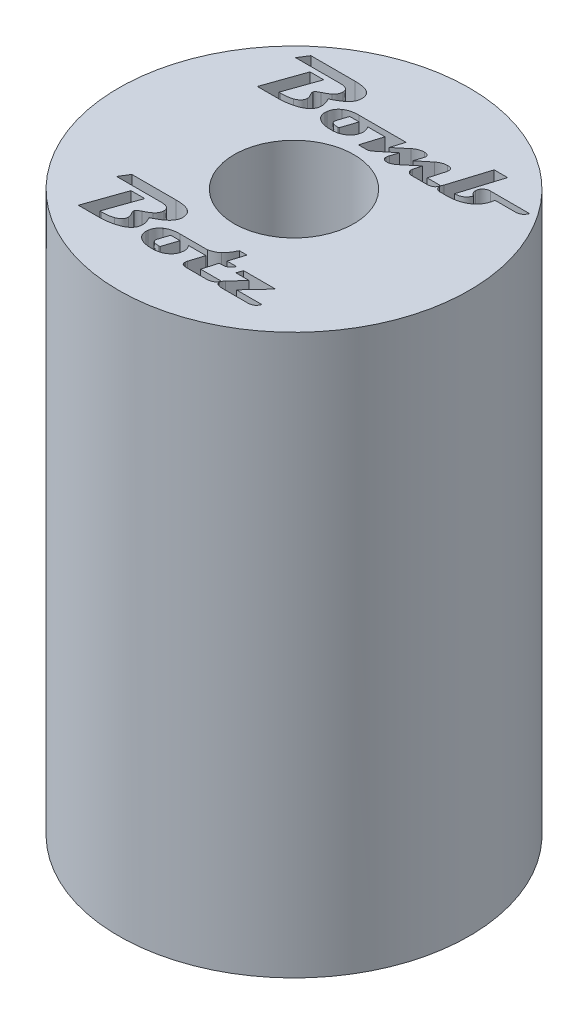
SolidWorks part; units mm, degrees
ref_plane "Front Plane" through (0, 0, 0) normal (0, 0, 1) x (1, 0, 0)
ref_plane "Top Plane" through (0, 0, 0) normal (0, 1, 0) x (1, 0, 0)
ref_plane "Right Plane" through (0, 0, 0) normal (1, 0, 0) x (0, 0, -1)
sketch "Sketch1" plane through (0, 0, 0) normal (0, 1, 0) x (1, 0, 0)
  circle A0 centre (0, 0) radius 10.414
  dimension "D1" = 20.828
extrude "Boss-Extrude1" add sketch "Sketch1" along normal blind 34.798
sketch "Sketch2" plane through (0, 34.798, 0) normal (0, 1, 0) x (1, 0, 0)
  circle A0 centre (0, 0) radius 3.556
  dimension "D1" = 7.112
extrude "Cut-Extrude1" cut sketch "Sketch2" against normal blind 34.798
sketch "Sketch3" plane through (0, 34.798, 0) normal (0, 1, 0) x (1, 0, 0)
  text T0 "Bomb" font "Magneto" height 3.175
extrude "Cut-Extrude2" cut sketch "Sketch3" against normal blind 2.54
sketch "Sketch4" plane through (0, 34.798, 0) normal (0, 1, 0) x (1, 0, 0)
  text T0 "Botz" font "Magneto" height 3.175
extrude "Cut-Extrude3" cut sketch "Sketch4" against normal blind 2.54
sketch "Sketch5" plane through (0, 0, 0) normal (0, -1, 0) x (-1, 0, 0)
  circle A0 centre (0, 0) radius 10.414
extrude "Cut-Extrude4" cut sketch "Sketch5" against normal blind 1.5875
